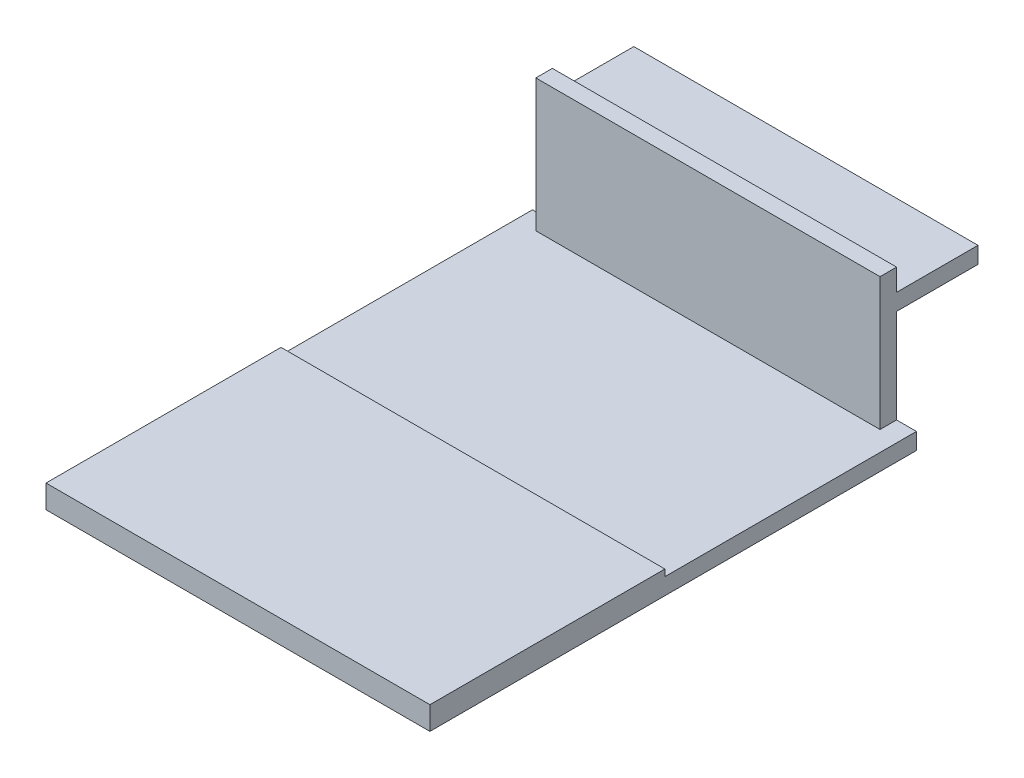
SolidWorks part; units mm, degrees
ref_plane "Front Plane" through (0, 0, 0) normal (0, 0, 1) x (1, 0, 0)
ref_plane "Top Plane" through (0, 0, 0) normal (0, 1, 0) x (1, 0, 0)
ref_plane "Right Plane" through (0, 0, 0) normal (1, 0, 0) x (0, 0, -1)
sketch "Sketch1" plane through (0, 0, 0) normal (0, 0, 1) x (1, 0, 0)
  line L1 (-30.1473, 17.4697) -> (101.9327, 17.4697)
  line L2 (-30.1473, 17.4697) -> (-30.1473, -39.6803)
  line L3 (-30.1473, -39.6803) -> (101.9327, -39.6803)
  line L4 (101.9327, 17.4697) -> (101.9327, -39.6803)
  dimension "D1" = 57.15
  dimension "D2" = 132.08
extrude "Boss-Extrude1" add sketch "Sketch1" along normal blind 6.35
sketch "Sketch2" plane through (0, 0, 0) normal (0, 0, -1) x (-1, 0, 0)
  line L0 (-101.9327, -39.6803) -> (-101.9327, 17.4697) construction
  line L1 (-101.9327, 2.7377) -> (30.1473, 2.7377)
  line L2 (-101.9327, 2.7377) -> (-101.9327, 9.0877)
  line L3 (-101.9327, 9.0877) -> (30.1473, 9.0877)
  line L4 (30.1473, 2.7377) -> (30.1473, 9.0877)
  line L5 (30.1473, 17.4697) -> (30.1473, -39.6803) construction
  line L6 (-35.8927, 9.0877) -> (-35.8927, 17.4697) construction
  line L8 (-101.9327, 17.4697) -> (30.1473, 17.4697) construction
  dimension "D1" = 8.382
  dimension "D2" = 6.35
extrude "Boss-Extrude2" add sketch "Sketch2" along normal blind 31.242
sketch "Sketch3" plane through (0, 0, 6.35) normal (0, 0, 1) x (1, 0, 0)
  line L0 (101.9327, -39.6803) -> (101.9327, 17.4697) construction
  line L1 (-30.1473, -39.6803) -> (101.9327, -39.6803)
  line L2 (-30.1473, -39.6803) -> (-30.1473, -33.3303)
  line L3 (-30.1473, -33.3303) -> (101.9327, -33.3303)
  line L4 (101.9327, -39.6803) -> (101.9327, -33.3303)
  dimension "D1" = 6.35
extrude "Boss-Extrude3" add sketch "Sketch3" along normal blind 180.34
sketch "Sketch4" plane through (0, -39.6803, 0) normal (0, -1, 0) x (1, 0, 0)
  line L0 (-30.1473, 186.69) -> (101.9327, 186.69) construction
  line L1 (-30.1473, 0) -> (-37.7673, 0)
  line L2 (-30.1473, 0) -> (-30.1473, 186.69)
  line L3 (-30.1473, 186.69) -> (-37.7673, 186.69)
  line L4 (-37.7673, 0) -> (-37.7673, 186.69)
  line L6 (101.9327, 0) -> (109.5527, 0)
  line L7 (101.9327, 0) -> (101.9327, 186.69)
  line L8 (101.9327, 186.69) -> (109.5527, 186.69)
  line L9 (109.5527, 0) -> (109.5527, 186.69)
  point P12 (109.5527, 186.0608)
  point P13 (0, 0)
  point P14 (101.9327, 186.69)
  point P16 (101.9327, 186.69)
  dimension "D1" = 7.62
  dimension "D2" = 7.62
extrude "Boss-Extrude4" add sketch "Sketch4" against normal blind 6.35
sketch "Sketch5" plane through (0, -33.3303, 0) normal (0, 1, 0) x (1, 0, 0)
  line L0 (35.8927, -6.35) -> (35.8927, -186.69) construction
  line L1 (101.9327, -6.35) -> (-30.1473, -6.35) construction
  line L2 (109.5527, -186.69) -> (-37.7673, -186.69) construction
  line L3 (35.8927, -96.52) -> (-37.7673, -96.52) construction
  line L4 (-37.7673, -186.69) -> (-37.7673, 0) construction
  line L6 (-37.7673, -96.52) -> (109.5527, -96.52)
  line L7 (-37.7673, -96.52) -> (-37.7673, -186.69)
  line L8 (-37.7673, -186.69) -> (109.5527, -186.69)
  line L9 (109.5527, -96.52) -> (109.5527, -186.69)
extrude "Boss-Extrude5" add sketch "Sketch5" along normal blind 2.54
